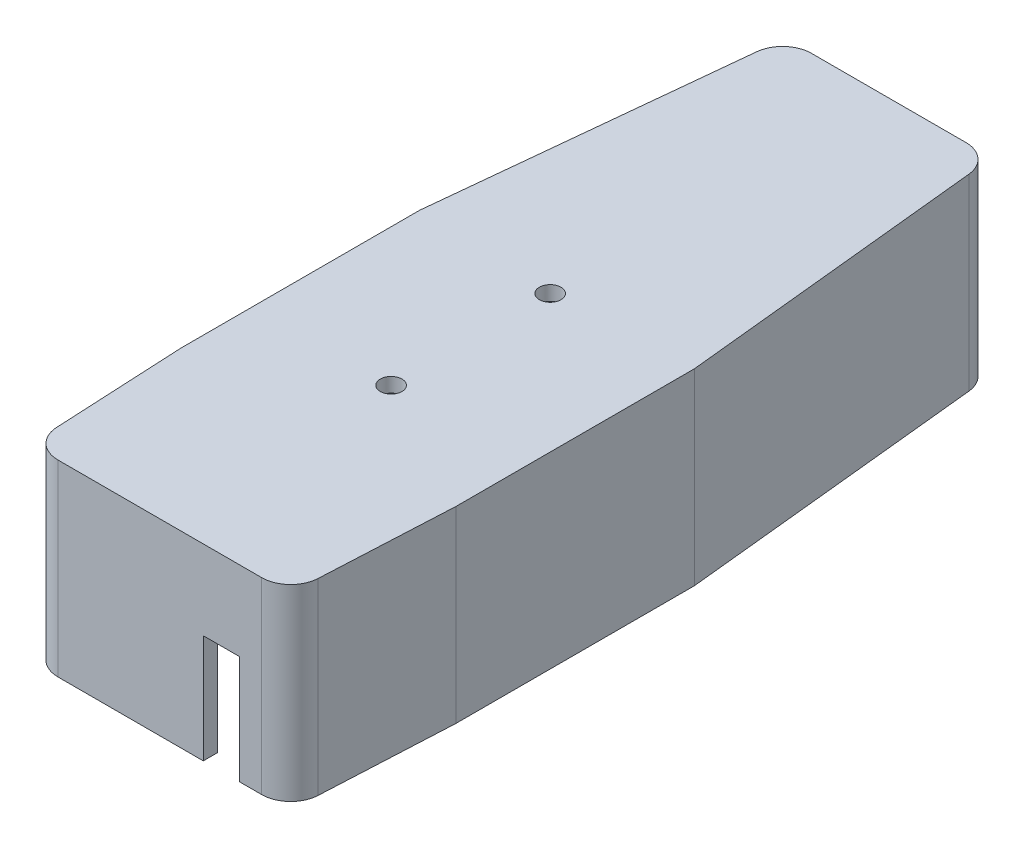
SolidWorks part; units mm, degrees
ref_plane "Front Plane" through (0, 0, 0) normal (0, 0, 1) x (1, 0, 0)
ref_plane "Top Plane" through (0, 0, 0) normal (0, 1, 0) x (1, 0, 0)
ref_plane "Right Plane" through (0, 0, 0) normal (1, 0, 0) x (0, 0, -1)
sketch "Sketch1" plane through (0, 0, 0) normal (0, 1, 0) x (1, 0, 0)
  line L8 (6.3059, 78.848) -> (27.6941, 78.848)
  line L9 (31.6734, 75.255) -> (36, 32.95)
  line L10 (36, -0.05) -> (36, 32.95)
  line L11 (35.0925, -18.1998) -> (36, -0.05)
  line L12 (2.9025, -22) -> (31.0975, -22)
  line L13 (-2, -0.05) -> (-1.0925, -18.1998)
  line L14 (-2, -0.05) -> (-2, 32.95)
  line L15 (2.3266, 75.255) -> (-2, 32.95)
  arc A4 (31.6734, 75.255) -> (27.6941, 78.848) centre (27.6941, 74.848) ccw
  arc A5 (31.0975, -22) -> (35.0925, -18.1998) centre (31.0975, -18) ccw
  arc A6 (-1.0925, -18.1998) -> (2.9025, -22) centre (2.9025, -18) ccw
  arc A7 (2.3266, 75.255) -> (6.3059, 78.848) centre (6.3059, 74.848) cw
  dimension "D1" = 33
  dimension "D2" = 33
extrude "Boss-Extrude1" add sketch "Sketch1" along normal blind 26
shell "Shell1" thickness 2
sketch "Sketch3" plane through (0, 0, 22) normal (0, 0, 1) x (1, 0, 0)
  line L0 (28.0089, 0) -> (28.0089, 15)
  line L1 (2.9025, 0) -> (31.0975, 0) construction
  line L2 (23.0089, 0) -> (23.0089, 15)
  line L3 (28.0089, 0) -> (23.0089, 0)
  line L4 (28.0089, 15) -> (23.0089, 15)
  dimension "D1" = 0
  dimension "D2" = 5
extrude "Cut-Extrude1" cut sketch "Sketch3" against normal blind 5
sketch "Sketch4" plane through (0, 24, 0) normal (0, -1, 0) x (1, 0, 0)
  line L0 (0, -32.848) -> (0, 0) construction
  line L3 (2.9025, 20) -> (31.0975, 20) construction
  circle A0 centre (17, -10) radius 1.5
  circle A1 centre (17, -32) radius 1.5
  point P6 (17, 20)
  dimension "D3" = 3
  dimension "D4" = 3
  dimension "D1" = 22
  dimension "D2" = 17
  dimension "D5" = 30
extrude "Cut-Extrude2" cut sketch "Sketch4" against normal blind 10
sketch "Sketch5" plane through (0, 0, 0) normal (0, -1, 0) x (1, 0, 0)
  line L1 (30.5227, -66.848) -> (3.4773, -66.848)
  line L2 (34, -32.848) -> (29.6837, -75.0515) construction
  line L3 (4.3163, -75.0515) -> (0, -32.848) construction
  line L4 (27.6941, -76.848) -> (6.3059, -76.848) construction
  line L5 (30.5227, -66.848) -> (29.6837, -75.0515)
  line L6 (27.6941, -76.848) -> (6.3059, -76.848)
  line L7 (4.3163, -75.0515) -> (3.4773, -66.848)
  arc A1 (27.6941, -76.848) -> (29.6837, -75.0515) centre (27.6941, -74.848) ccw construction
  arc A2 (27.6941, -76.848) -> (29.6837, -75.0515) centre (27.6941, -74.848) ccw
  arc A3 (4.3163, -75.0515) -> (6.3059, -76.848) centre (6.3059, -74.848) ccw construction
  arc A4 (4.3163, -75.0515) -> (6.3059, -76.848) centre (6.3059, -74.848) ccw
  dimension "D2" = 10
extrude "Boss-Extrude2" add sketch "Sketch5" against normal blind 3
sketch "Sketch7" plane through (0, 0, 0) normal (0, -1, 0) x (1, 0, 0)
  circle A0 centre (24.3355, -71.848) radius 1.397
extrude "Cut-Extrude3" cut sketch "Sketch7" against normal blind 5
sketch "Sketch8" plane through (0, 0, 0) normal (0, -1, 0) x (1, 0, 0)
  circle A0 centre (9.3362, -71.848) radius 1.397
extrude "Cut-Extrude4" cut sketch "Sketch8" against normal blind 5
